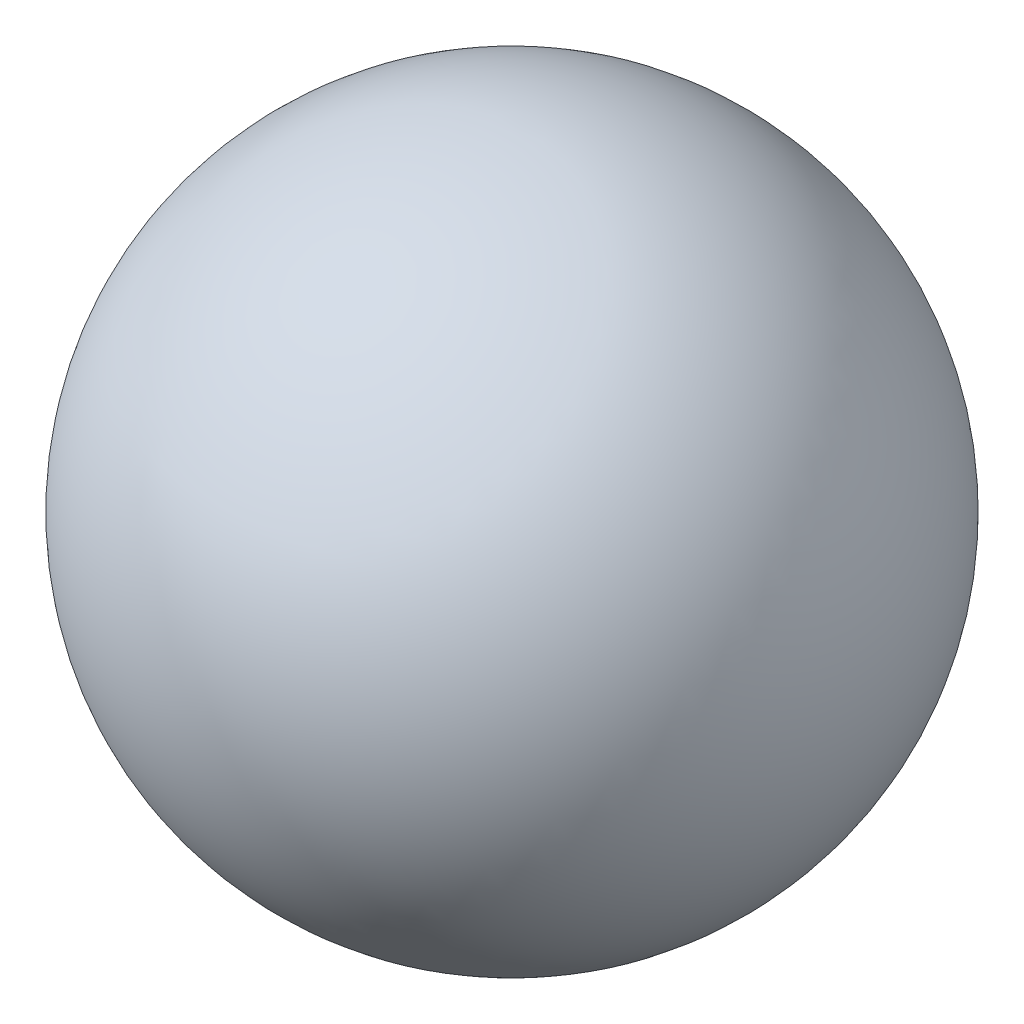
SolidWorks part; units mm, degrees
ref_plane "前视基准面" through (0, 0, 0) normal (0, 0, 1) x (1, 0, 0)
ref_plane "上视基准面" through (0, 0, 0) normal (0, 1, 0) x (1, 0, 0)
ref_plane "右视基准面" through (0, 0, 0) normal (1, 0, 0) x (0, 0, -1)
sketch "草图1" plane through (0, 0, 0) normal (0, 0, 1) x (1, 0, 0)
  line L0 (0, -35) -> (0, 35)
  arc A0 (0, -35) -> (0, 35) centre (0, 0) ccw
  point P6 (0, 0)
revolve "球体" add sketch "草图1" angle 360 about L0
